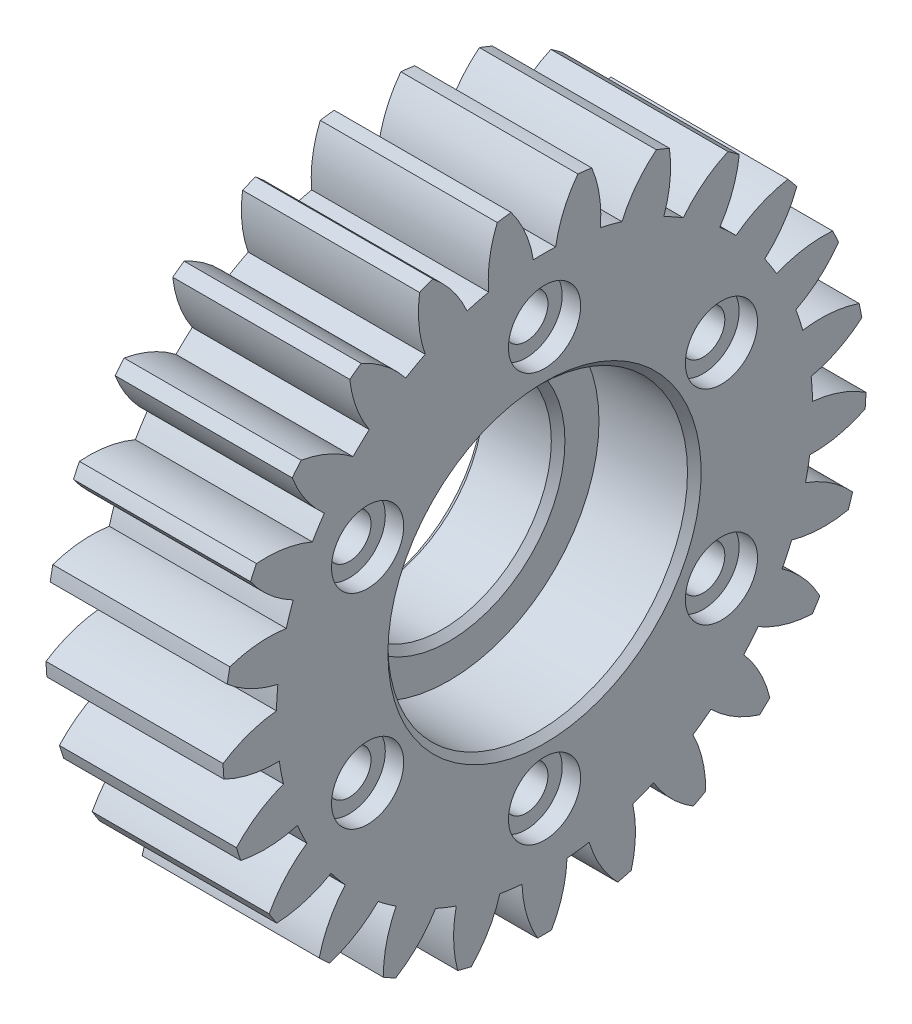
SolidWorks part; units mm, degrees
ref_plane "Plane1" through (0, 0, 0) normal (0, 0, 1) x (1, 0, 0)
ref_plane "Plane2" through (0, 0, 0) normal (0, 1, 0) x (1, 0, 0)
ref_plane "Plane3" through (0, 0, 0) normal (1, 0, 0) x (0, 0, -1)
sketch "HoldingSke" plane through (0, 0, 0) normal (0, 1, 0) x (1, 0, 0)
  line L0 (0, 0) -> (0.5179, -0.2415)
  line L1 (-15, 0) -> (100, 0) construction
  line L2 (0, 0) -> (-2.1039, 2.3779)
  line L3 (0, 0) -> (-11.863, 4.5341)
  line L4 (0, 0) -> (7.8269, 3.6497)
  line L5 (0, 0) -> (-46.8476, -17.4728)
  line L6 (0, 0) -> (-10.7765, -7.2709)
  line L7 (-2.1039, 2.3779) -> (8.6586, 51.2059)
  line L8 (-76.2, 54.61) -> (-74.8, 54.61)
  line L9 (-71.009, 38.7566) -> (-53.1078, 45.2721)
  line L10 (-76.2, 71.12) -> (104.1128, 71.12)
  line L11 (0, 0) -> (-13, 0)
  line L12 (-76.2, 101.6) -> (-76.147, 101.6)
  line L13 (24.9733, 27.94) -> (52.9518, 28.4284)
  line L14 (24.9733, 27.94) -> (24.9743, 27.94)
  line L15 (24.9733, 27.94) -> (100.4006, 29.5858)
  line L16 (-63.627, -1.75) -> (-12.827, -1.75)
  circle A0 centre (0, 0) radius 4
  circle A1 centre (0, 0) radius 19.6865
  circle A2 centre (0, 0) radius 37.5
  circle A3 centre (0, 0) radius 4
  dimension "MHD" = 39.373
  dimension "Hub_dia" = 75
  dimension "Bore" = 8
  dimension "MBD" = 8
  dimension "Num_teeth" = 25
  dimension "Pitch" = 0.5714
  dimension "Overall_len" = 50
  dimension "Show_teeth" = 25
  dimension "Thickness" = 13
  dimension "OAL" = 50.0001
  dimension "T_dim" = 1.4
  dimension "Ap" = 20
  dimension "H" = 19.05
  dimension "Pitch_radius" = 180.3128
  dimension "Width" = 13
  dimension "Backlash" = 0.053
  dimension "Addendum_fac" = 1
  dimension "Dedendum_fac" = 1.25
  dimension "Clearance_fac" = 0.25
  dimension "Dedendum_add" = 0.001
  dimension "Module" = 1.75
sketch "BasProSke" plane through (0, 0, 0) normal (0, 1, 0) x (1, 0, 0)
  line L0 (-10, 0) -> (60, 0) construction
  line L1 (0, 0) -> (0, 23.625)
  line L2 (0, 0) -> (13, 0)
  line L3 (13, 0) -> (13, 23.625)
  line L4 (13, 23.625) -> (0, 23.625)
  dimension "Thickness" = 13
  dimension "Diameter" = 47.25
revolve "Base-Revolve" add sketch "BasProSke" angle 360 about L0
sketch "TooCutSke" plane through (0, 0, 0) normal (1, 0, 0) x (0, 0, -1)
  line L1 (0, 0) -> (0, 107) construction
  line L2 (0, 0) -> (-1.4663, 21.8258) construction
  line L3 (0, 0) -> (-5.4739, 43.3306) construction
  line L4 (-1.4663, 21.8258) -> (-2.737, 21.6653) construction
  arc A0 (0.819, 19.6695) -> (-0.819, 19.6695) centre (0, 0) ccw
  arc A1 (2.4674, 23.5213) -> (-2.4674, 23.5213) centre (0, 0) ccw
  circle A2 centre (0, 0) radius 21.875 construction
  circle A3 centre (0, 0) radius 20.5558 construction
  arc A4 (-0.819, 19.6695) -> (-2.4674, 23.5213) centre (-9.4536, 18.2529) ccw
  arc A5 (2.4674, 23.5213) -> (0.819, 19.6695) centre (9.4536, 18.2529) ccw
  dimension "Root_dia" = 39.373
  dimension "Overcut_dia" = 47.3008
  dimension "Pitch_dia" = 43.75
  dimension "Base_dia" = 41.1116
  dimension "Flank_rad" = 8.75
  dimension "Half_ang" = 7.2
  dimension "Half_CT" = 1.2808
extrude "ToothCut" cut sketch "TooCutSke" along normal through all
fillet "Breaks" [suppressed] radius 0.035
fillet "RootFillets" [suppressed] radius 0.4385
pattern_circular "TeethCuts" count 25 every 14.4 about axis through (-10, 0, 0) along (1, 0, 0) of "ToothCut", "RootFillets", "Breaks"
sketch "HubNeaOneSke" plane through (0, 0, 0) normal (-1, 0, 0) x (0, 0, 1)
  circle A0 centre (0, 0) radius 19.6865
  dimension "Diameter" = 39.373
extrude "HubNearOne" [suppressed] add sketch "HubNeaOneSke" along normal blind 37.0001
sketch "HubNeaBotSke" plane through (0, 0, 0) normal (-1, 0, 0) x (0, 0, 1)
  circle A0 centre (0, 0) radius 19.6865
  dimension "Diameter" = 39.373
extrude "HubNearBoth" [suppressed] add sketch "HubNeaBotSke" along normal blind 18.5
ref_plane "FarPln" through (13, 0, 0) normal (1, 0, 0) x (0, 0, -1)
sketch "HubFarSke" plane through (13, 0, 0) normal (1, 0, 0) x (0, 0, -1)
  circle A0 centre (0, 0) radius 19.6865
  dimension "Diameter" = 39.373
extrude "HubFar" [suppressed] add sketch "HubFarSke" along normal blind 18.5
sketch "BorSke" plane through (0, 0, 0) normal (1, 0, 0) x (0, 0, -1)
  circle A0 centre (0, 0) radius 4
  dimension "Diameter" = 8
extrude "Bore" cut sketch "BorSke" along normal mid plane 100.0001
sketch "KeySke" plane through (0, 0, 0) normal (1, 0, 0) x (0, 0, -1)
  line L0 (-1.5, 0) -> (-1.5, 5.4)
  line L1 (-1.5, 5.4) -> (1.5, 5.4)
  line L2 (1.5, 5.4) -> (1.5, 0)
  line L3 (0, 0) -> (0, 34) construction
  line L4 (-1.5, 0) -> (1.5, 0)
  dimension "Offset" = 5.4
  dimension "Width" = 3
extrude "Keyway" [suppressed] cut sketch "KeySke" along normal mid plane 100.0001
pattern_circular "Keyway2" [suppressed] count 2 every 90 about axis through (-10, 0, 0) along (1, 0, 0)
sketch "Sketch1" plane through (13, 0, 0) normal (1, 0, 0) x (0, 0, -1)
  circle A0 centre (0, 0) radius 11
  dimension "D1" = 22
extrude "Cut-Extrude1" cut sketch "Sketch1" against normal blind 7
sketch "Sketch2" plane through (6, 0, 0) normal (1, 0, 0) x (0, 0, -1)
  circle A0 centre (0, 0) radius 8
  dimension "D1" = 16
extrude "Cut-Extrude2" cut sketch "Sketch2" against normal up to next
sketch "Sketch3" plane through (13, 0, 0) normal (1, 0, 0) x (0, 0, -1)
  line L0 (0, 0) -> (0, 6.9607) construction
  circle A0 centre (0, 15) radius 1.6
  dimension "D1" = 3.2
  dimension "D2" = 15
extrude "Cut-Extrude3" cut sketch "Sketch3" against normal up to next
pattern_circular "CirPattern1" count 6 over 360 about axis through (0, 0, 0) along (1, 0, 0) of "Cut-Extrude3"
chamfer "Chamfer1" distance 0.5 angle 45 3 edges at (6, 0, -8) (13, 0, -11) (0, 0, -8)
sketch "Sketch4" plane through (0, 0, 0) normal (-1, 0, 0) x (0, 0, 1)
  line L0 (0, 15) -> (0, 0) construction
  line L1 (1.6166, 17.8) -> (-1.6166, 17.8)
  line L2 (-1.6166, 17.8) -> (-3.2332, 15)
  line L3 (-3.2332, 15) -> (-1.6166, 12.2)
  line L4 (-1.6166, 12.2) -> (1.6166, 12.2)
  line L5 (1.6166, 12.2) -> (3.2332, 15)
  line L6 (3.2332, 15) -> (1.6166, 17.8)
  line L8 (-11.3738, 10.3) -> (-14.607, 10.3)
  line L9 (-14.607, 10.3) -> (-16.2235, 7.5)
  line L10 (-16.2235, 7.5) -> (-14.607, 4.7)
  line L11 (-14.607, 4.7) -> (-11.3738, 4.7)
  line L12 (-11.3738, 4.7) -> (-9.7572, 7.5)
  line L13 (-9.7572, 7.5) -> (-11.3738, 10.3)
  line L14 (11.3738, 10.3) -> (9.7572, 7.5)
  line L15 (9.7572, 7.5) -> (11.3738, 4.7)
  line L16 (11.3738, 4.7) -> (14.607, 4.7)
  line L17 (14.607, 4.7) -> (16.2235, 7.5)
  line L18 (16.2235, 7.5) -> (14.607, 10.3)
  line L19 (14.607, 10.3) -> (11.3738, 10.3)
  circle A0 centre (0, 15) radius 2.8 construction
  circle A1 centre (-12.9904, 7.5) radius 2.8 construction
  circle A2 centre (12.9904, 7.5) radius 2.8 construction
  dimension "D1" = 5.6
extrude "Cut-Extrude4" cut sketch "Sketch4" against normal blind 2.3
mirror "Mirror1" about plane through (0, 0, 0) normal (0, 1, 0) of "Cut-Extrude4"
sketch "Sketch6" plane through (13, 0, 0) normal (1, 0, 0) x (0, 0, -1)
  circle A0 centre (0, 15) radius 2.65
  dimension "D1" = 5.3
extrude "Cut-Extrude5" cut sketch "Sketch6" against normal blind 1.35
pattern_circular "CirPattern2" count 6 over 360 about axis through (0, 0, 0) along (1, 0, 0) of "Cut-Extrude5"
equation "' \"Module@HoldingSke\" = 6.35"
equation "' \"Num_teeth@HoldingSke\" = 12"
equation "' \"Ap@HoldingSke\" =  20"
equation "' \"Ap@HoldingSke\" = 20"
equation "' \"Width@HoldingSke\" = 0.5 * 25.4"
equation "' \"Hub_dia@HoldingSke\"= 1 * 25.4"
equation "' \"Hub_dia@HoldingSke\" = 1 * 25.4"
equation "' \"Overall_len@HoldingSke\" = 1.0 * 25.4"
equation "' \"Bore@HoldingSke\" = 0.75 * 25.4"
equation "' \"T_dim@HoldingSke\" = 0.1 * 25.4"
equation "' \"Width@KeySke\" = 0.25 * 25.4"
equation "' \"Show_teeth@HoldingSke\" = 13"
equation "' \"Backlash@HoldingSke\" = 0.009 * 25.4"
equation "' \"Addendum_fac@HoldingSke\" = 1.0"
equation "' \"Dedendum_fac@HoldingSke\" = 1.25"
equation "' \"Dedendum_add@HoldingSke\" = 0.00005 * 25.4"
equation "' \"Clearance_fac@HoldingSke\" = 0.25"
equation "\"Pitch@HoldingSke\" = 1 / \"Module@HoldingSke\""
equation "\"Overcut_dia@TooCutSke\" = (\"Num_teeth@HoldingSke\" + 2 * \"Addendum_fac@HoldingSke\") / \"Pitch@HoldingSke\" + 0.002 * 25.4"
equation "\"Pitch_dia@TooCutSke\" = \"Num_teeth@HoldingSke\" / \"Pitch@HoldingSke\""
equation "\"Base_dia@TooCutSke\" = \"Num_teeth@HoldingSke\" / \"Pitch@HoldingSke\" * cos((\"Ap@HoldingSke\"  * 3.14159265 / 180))"
equation "\"Root_dia@TooCutSke\" = (\"Num_teeth@HoldingSke\" + 2) / \"Pitch@HoldingSke\" - 2 * (\"Addendum_fac@HoldingSke\" + \"Dedendum_fac@HoldingSke\") / \"Pitch@HoldingSke\" - \"Dedendum_add@HoldingSke\" * 2"
equation "\"Half_ang@TooCutSke\" = 180 / \"Num_teeth@HoldingSke\""
equation "\"Half_CT@TooCutSke\" = \"Num_teeth@HoldingSke\" / \"Pitch@HoldingSke\" * sin((3.14159265 / 2 / \"Num_teeth@HoldingSke\")) / 2 - 7 * \"Backlash@HoldingSke\" / 4"
equation "\"Flank_rad@TooCutSke\" = \"Num_teeth@HoldingSke\" / \"Pitch@HoldingSke\" / 5"
equation "\"Radius@RootFillets\" = \"Clearance_fac@HoldingSke\" / \"Pitch@HoldingSke\" + \"Dedendum_add@HoldingSke\""
equation "\"Break_rad@Breaks\" = 0.02 / \"Pitch@HoldingSke\""
equation "\"Thickness@HoldingSke\" = \"Width@HoldingSke\""
equation "\"OAL@HoldingSke\" = \"Thickness@HoldingSke\""
equation "\"MHD@HoldingSke\" = (\"Num_teeth@HoldingSke\" + 2) / \"Pitch@HoldingSke\" - 2 * (\"Addendum_fac@HoldingSke\" + \"Dedendum_fac@HoldingSke\")  / \"Pitch@HoldingSke\" - \"Dedendum_add@HoldingSke\" * 2"
equation "\"MBD@HoldingSke\" = (\"Num_teeth@HoldingSke\" + 2) / \"Pitch@HoldingSke\" - 2 * (\"Addendum_fac@HoldingSke\" + \"Dedendum_fac@HoldingSke\")  / \"Pitch@HoldingSke\" - \"Dedendum_add@HoldingSke\" * 2 - 0.002 * 25.4"
equation "\"MHD@HoldingSke\" = ((sgn( \"MHD@HoldingSke\" - \"Hub_dia@HoldingSke\" )-1)*( \"MHD@HoldingSke\" - \"Hub_dia@HoldingSke\" ))/-2+ \"Hub_dia@HoldingSke\""
equation "\"MBD@HoldingSke\" = ((sgn( \"MBD@HoldingSke\" - \"Bore@HoldingSke\" )-1)*( \"MBD@HoldingSke\" - \"Bore@HoldingSke\" ))/-2+ \"Bore@HoldingSke\""
equation "\"OAL@HoldingSke\" = ((sgn( \"OAL@HoldingSke\" - \"Overall_len@HoldingSke\" )+1)*( \"OAL@HoldingSke\" - \"Overall_len@HoldingSke\" ))/2 + \"Overall_len@HoldingSke\" + 0.000002 * 25.4"
equation "\"Num_teeth@TeethCuts\" = int( \"Show_teeth@HoldingSke\" ) + 1"
equation "\"Num_teeth@TeethCuts\" = ((sgn( \"Num_teeth@TeethCuts\" - \"Num_teeth@HoldingSke\" )-1)*( \"Num_teeth@TeethCuts\" - \"Num_teeth@HoldingSke\" ))/-2+ \"Num_teeth@HoldingSke\""
equation "\"Num_teeth@TeethCuts\" = ((sgn( \"Num_teeth@TeethCuts\" - 2.0)+1)*( \"Num_teeth@TeethCuts\" - 2.0))/2 +2.0"
equation "\"Angle@TeethCuts\" = 360.0 / \"Num_teeth@HoldingSke\""
equation "\"Diameter@BasProSke\" = (\"Num_teeth@HoldingSke\" + 2 * \"Addendum_fac@HoldingSke\") / \"Pitch@HoldingSke\""
equation "\"Thickness@BasProSke\"  = \"Thickness@HoldingSke\""
equation "' \"Fillet_rad@BasProSke\" =  \"Thickness@HoldingSke\" * 0.05"
equation "' \"Fillet_rad@BasProSke\" = \"Thickness@HoldingSke\" * 0.05"
equation "\"MHD@HoldingSke\" = ((sgn( \"MHD@HoldingSke\" - \"Root_dia@TooCutSke\" )-1)*( \"MHD@HoldingSke\" - \"Root_dia@TooCutSke\" ))/-2+ \"Root_dia@TooCutSke\""
equation "\"Diameter@HubNeaOneSke\" = \"MHD@HoldingSke\""
equation "\"Length@HubNearOne\" = \"OAL@HoldingSke\" - \"Thickness@BasProSke\""
equation "\"Diameter@HubNeaBotSke\" = \"MHD@HoldingSke\""
equation "\"Length@HubNearBoth\" = ( \"OAL@HoldingSke\" - \"Thickness@BasProSke\" ) / 2.0"
equation "\"Thickness@FarPln\" = \"Thickness@BasProSke\""
equation "\"Diameter@HubFarSke\" = \"MHD@HoldingSke\""
equation "\"Length@HubFar\" = ( \"OAL@HoldingSke\" - \"Thickness@BasProSke\" ) / 2.0"
equation "\"Diameter@BorSke\" = \"MBD@HoldingSke\""
equation "\"D1@Bore\" = \"OAL@HoldingSke\" * 2.0"
equation "\"D1@Keyway\" = \"OAL@HoldingSke\" * 2.0"
equation "\"Offset@KeySke\" = \"T_dim@HoldingSke\" + \"MBD@HoldingSke\" / 2.0"
